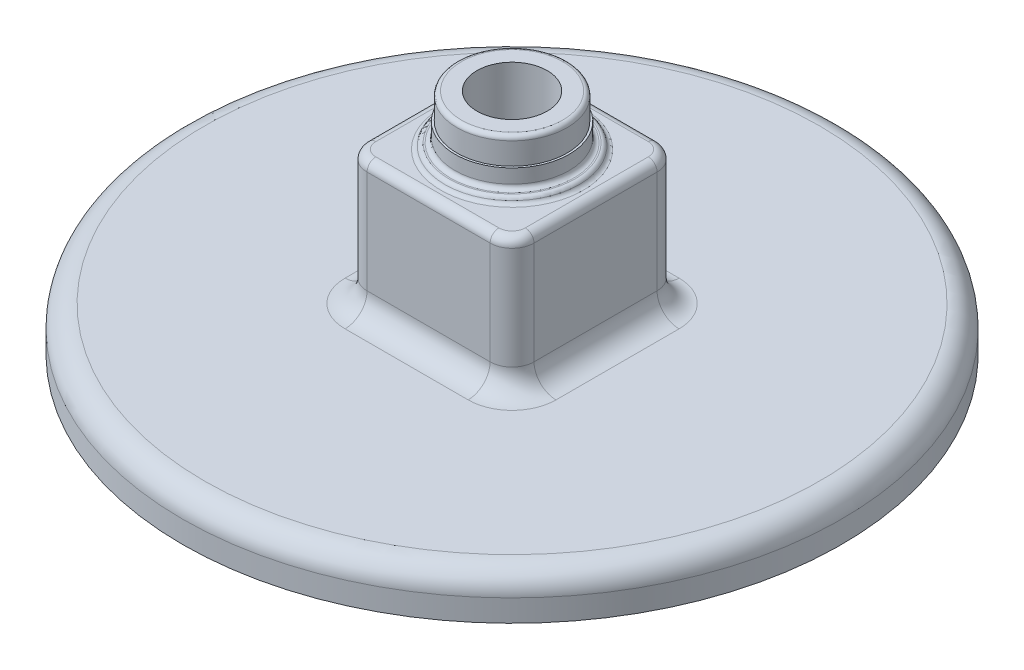
SolidWorks part; units mm, degrees
material "ABS"
ref_plane "정면" through (0, 0, 0) normal (0, 0, 1) x (1, 0, 0)
ref_plane "윗면" through (0, 0, 0) normal (0, 1, 0) x (1, 0, 0)
ref_plane "우측면" through (0, 0, 0) normal (1, 0, 0) x (0, 0, -1)
sketch "Sketch1" plane through (0, 0, 0) normal (0, 1, 0) x (1, 0, 0)
  line L1 (-190, -190) -> (190, -190)
  line L2 (-190, -190) -> (-190, 190)
  line L3 (-190, 190) -> (190, 190)
  line L4 (190, -190) -> (190, 190)
  line L5 (-190, -190) -> (190, 190) construction
  line L6 (-190, 190) -> (190, -190) construction
  point P0 (0, 0)
  dimension "D1" = 380
extrude "Extrude1" add sketch "Sketch1" along normal blind 404
sketch "Sketch4" plane through (0, 0, 0) normal (0, 1, 0) x (1, 0, 0)
  circle A0 centre (0, 0) radius 750
  dimension "D1" = 1500
extrude "Extrude2" add sketch "Sketch4" along normal blind 100
fillet "Fillet1" radius 50 4 edges at (-190, 252, 190) (-190, 252, -190) (190, 252, -190) (190, 252, 190)
sketch "Sketch2" plane through (0, 0, 0) normal (1, 0, 0) x (0, 0, -1)
  line L0 (0, 0) -> (0, 519) construction
  line L1 (125.25, 459) -> (130, 459)
  line L2 (0, 519) -> (125.25, 519)
  line L3 (0, 519) -> (0, 404)
  line L4 (0, 404) -> (152, 404)
  line L5 (125.25, 519) -> (125.25, 459)
  line L6 (130, 459) -> (130, 417)
  line L7 (130, 417) -> (152, 417)
  line L8 (152, 417) -> (152, 404)
  line L9 (140, 404) -> (-140, 404) construction
  dimension "D1" = 152
  dimension "D2" = 130
  dimension "D3" = 125.25
  dimension "D4" = 13
  dimension "D5" = 55
  dimension "D6" = 115
revolve "Revolve1" add sketch "Sketch2" angle 360 about L0
sketch "Sketch3" plane through (0, 0, 0) normal (1, 0, 0) x (0, 0, -1)
  line L0 (0, 0) -> (0, 519) construction
  line L2 (0, 519) -> (80, 519)
  line L3 (0, 519) -> (0, 0)
  line L4 (0, 0) -> (40, 0)
  line L5 (80, 519) -> (80, 269)
  line L6 (125.25, 519) -> (-125.25, 519) construction
  line L7 (40, 169) -> (40, 0)
  line L8 (17.5, 269) -> (80, 269)
  line L9 (17.5, 269) -> (17.5, 169)
  line L10 (17.5, 169) -> (40, 169)
  line L12 (-140, 0) -> (140, 0) construction
  dimension "D1" = 17.5
  dimension "D2" = 80
  dimension "D3" = 100
  dimension "D4" = 250
  dimension "D5" = 40
revolve "Cut-Revolve1" cut sketch "Sketch3" angle 360 about L0
fillet "Fillet2" radius 50 1 edges at (0, 100, 750)
fillet "Fillet3" radius 50 8 edges at (175.3553, 100, 175.3553) (0, 100, 190) (-175.3553, 100, 175.3553) (-190, 100, 0) (-175.3553, 100, -175.3553) (0, 100, -190) (175.3553, 100, -175.3553) (190, 100, 0)
fillet "Fillet4" radius 20 8 edges at (175.3553, 404, 175.3553) (0, 404, 190) (-175.3553, 404, 175.3553) (-190, 404, 0) (-175.3553, 404, -175.3553) (0, 404, -190) (175.3553, 404, -175.3553) (190, 404, 0)
fillet "Fillet5" radius 10 1 edges at (0, 519, -125.25)
fillet "Fillet6" radius 10 2 edges at (0, 417, -130) (0, 404, -152)
fillet "Fillet7" radius 10 1 edges at (0, 417, -152)
scale "Scale1" bodies to scale 103 scale about origin uniform scaling yes scale factor 0.1
equation "\"Mass\"= \"SW-질량\" / 1000"
